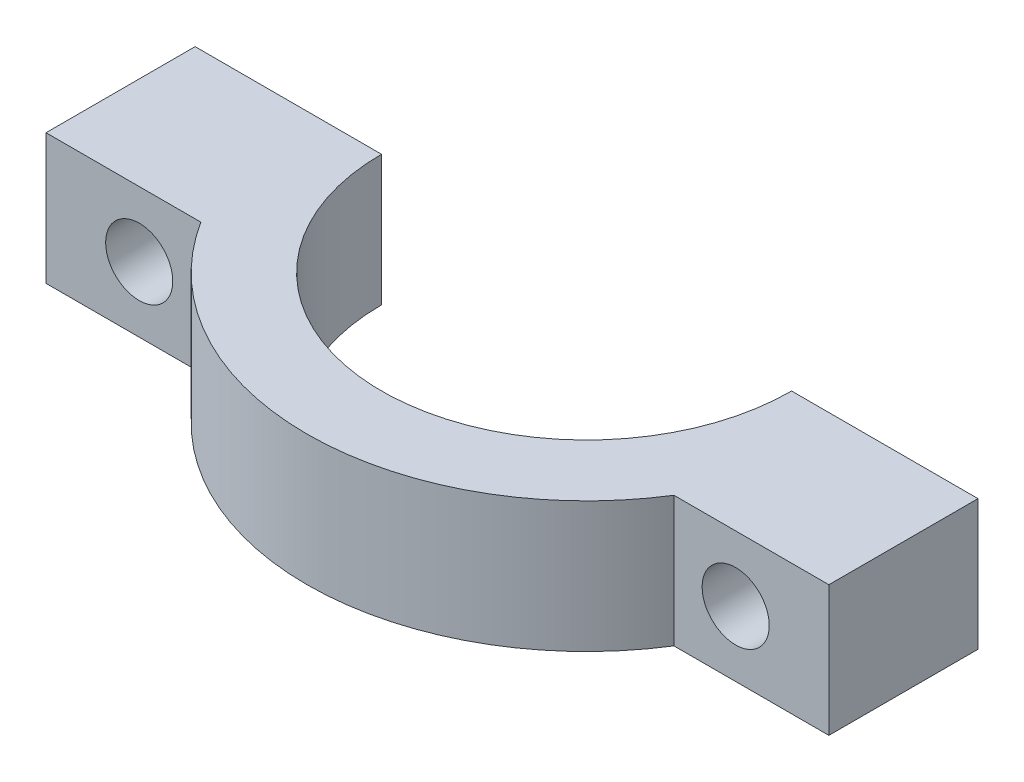
SolidWorks part; units mm, degrees
ref_plane "Front Plane" through (0, 0, 0) normal (0, 0, 1) x (1, 0, 0)
ref_plane "Top Plane" through (0, 0, 0) normal (0, 1, 0) x (1, 0, 0)
ref_plane "Right Plane" through (0, 0, 0) normal (1, 0, 0) x (0, 0, -1)
sketch "Sketch3" plane through (0, 0, 0) normal (0, 1, 0) x (1, 0, 0)
  line L0 (-11, 0) -> (-21, 0)
  line L1 (-21, 0) -> (-21, -8)
  line L2 (-21, -8) -> (-12.6886, -8)
  line L3 (0, 0) -> (0, -15) construction
  line L4 (21, -8) -> (12.6886, -8)
  line L5 (21, 0) -> (21, -8)
  line L6 (11, 0) -> (21, 0)
  arc A0 (-12.6886, -8) -> (12.6886, -8) centre (0, 0) ccw
  arc A1 (-11, 0) -> (11, 0) centre (0, 0) ccw
  dimension "D1" = 30
  dimension "D2" = 22
  dimension "D3" = 10
  dimension "D4" = 8
extrude "Boss-Extrude1" add sketch "Sketch3" along normal blind 7
sketch "Sketch4" plane through (0, 0, 0) normal (0, 0, 1) x (1, 0, 0)
  circle A1 centre (16, 3.5) radius 1.8
extrude "Cut-Extrude3" cut sketch "Sketch4" along normal through all both contours A1
mirror "Mirror1" about plane through (0, 0, 0) normal (1, 0, 0) of "Cut-Extrude3"
